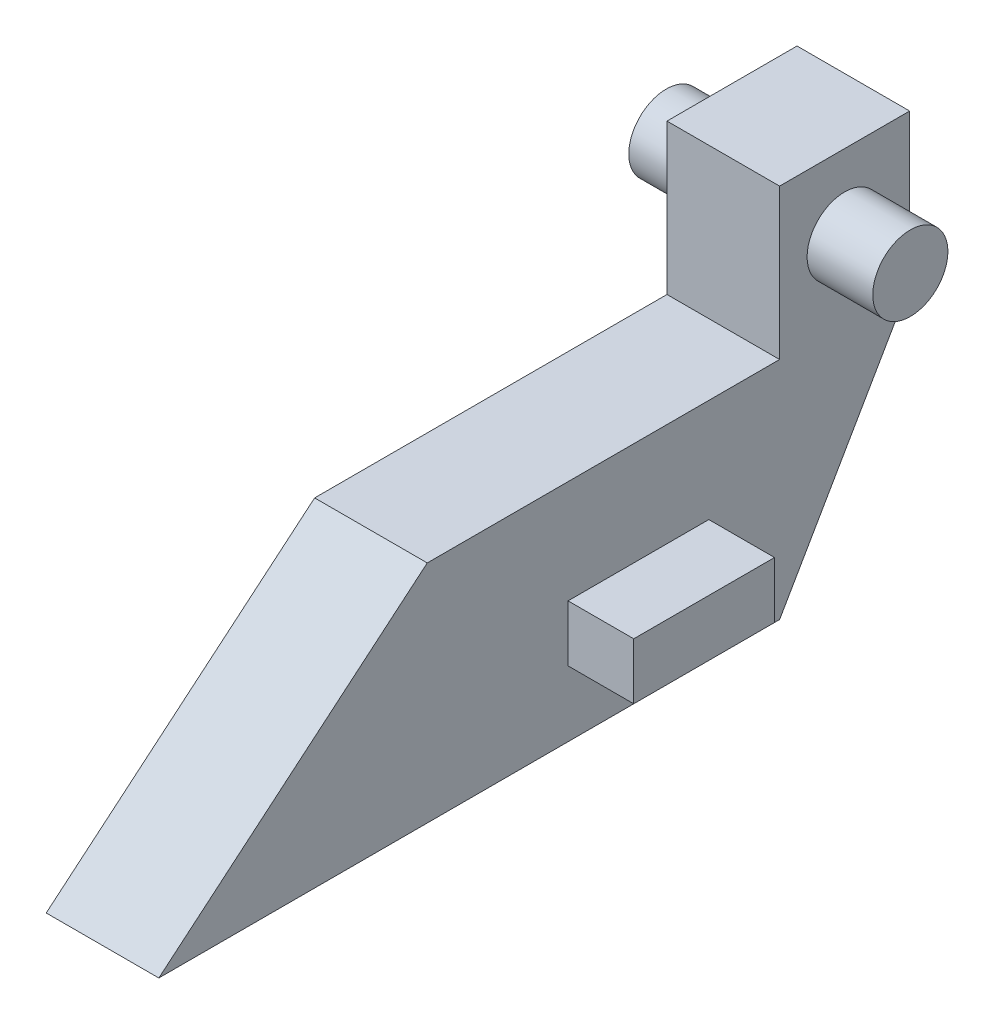
SolidWorks part; units mm, degrees
ref_plane "Front Plane" through (0, 0, 0) normal (0, 0, 1) x (1, 0, 0)
ref_plane "Top Plane" through (0, 0, 0) normal (0, 1, 0) x (1, 0, 0)
ref_plane "Right Plane" through (0, 0, 0) normal (1, 0, 0) x (0, 0, -1)
sketch "Sketch1" plane through (0, 0, 0) normal (0, 0, 1) x (1, 0, 0)
  line L1 (-6, 24) -> (6, 24)
  line L2 (-6, 24) -> (-6, 0)
  line L3 (-6, 0) -> (6, 0)
  line L4 (6, 24) -> (6, 0)
  point P4 (0, 24)
  dimension "D1" = 12
  dimension "D2" = 24
extrude "Boss-Extrude1" add sketch "Sketch1" against normal blind 80
sketch "Sketch2" plane through (6, 0, 0) normal (1, 0, 0) x (0, 0, -1)
  line L0 (0, 0) -> (28.6021, 24)
  line L1 (80, 24) -> (0, 24) construction
  line L2 (80, 24) -> (66.1436, 0)
  line L3 (80, 0) -> (0, 0) construction
  line M3 (0, 24) -> (0, 0)
  line M4 (0, 0) -> (80, 0)
  line M5 (80, 0) -> (80, 24)
  line M6 (80, 24) -> (0, 24)
  dimension "D1" = 40
  dimension "D2" = 60
extrude "Cut-Extrude1" cut sketch "Sketch2" against normal blind 52 contours L0 M3 M6 | L2 M5 M4
sketch "Sketch3" plane through (6, 0, 0) normal (1, 0, 0) x (0, 0, -1)
  line L0 (66.1436, 0) -> (0, 0) construction
  line L1 (43.6021, 13) -> (58.6021, 13)
  line L2 (43.6021, 13) -> (43.6021, 7)
  line L3 (43.6021, 7) -> (58.6021, 7)
  line L4 (58.6021, 13) -> (58.6021, 7)
  dimension "D1" = 15
  dimension "D2" = 15
  dimension "D3" = 6
  dimension "D4" = 7
extrude "Boss-Extrude2" add sketch "Sketch3" along normal blind 7
mirror "Mirror1" about plane through (0, 0, 0) normal (1, 0, 0) of "Boss-Extrude2"
sketch "Sketch4" plane through (0, 24, 0) normal (0, 1, 0) x (1, 0, 0)
  line L1 (-6, 80) -> (6, 80)
  line L2 (-6, 80) -> (-6, 66.1436)
  line L3 (-6, 66.1436) -> (6, 66.1436)
  line L4 (6, 80) -> (6, 66.1436)
extrude "Boss-Extrude3" add sketch "Sketch4" along normal blind 16
sketch "Sketch6" plane through (0, 0, 0) normal (1, 0, 0) x (0, 0, -1)
  circle A0 centre (73.0718, 32) radius 4
  dimension "D1" = 8
extrude "Boss-Extrude4" add sketch "Sketch6" along normal mid plane 26
